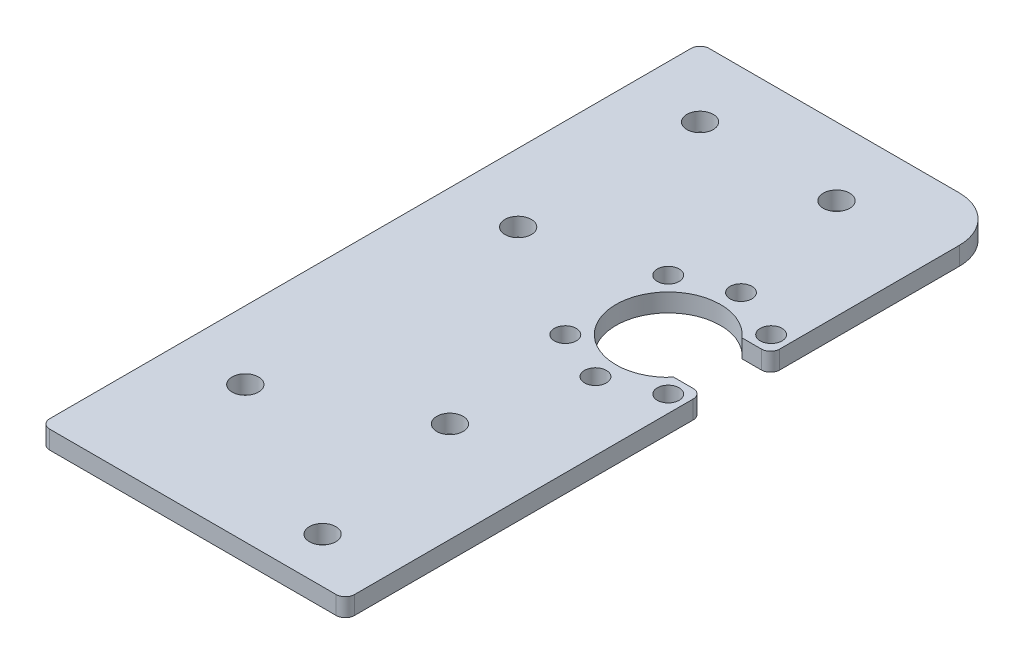
SolidWorks part; units mm, degrees
ref_plane "Front Plane" through (0, 0, 0) normal (0, 0, 1) x (1, 0, 0)
ref_plane "Top Plane" through (0, 0, 0) normal (0, 1, 0) x (1, 0, 0)
ref_plane "Right Plane" through (0, 0, 0) normal (1, 0, 0) x (0, 0, -1)
sketch "Sketch1" plane through (0, 0, 0) normal (0, 1, 0) x (1, 0, 0)
  line L1 (0, 0) -> (67, 0)
  line L2 (0, 0) -> (0, 145)
  line L3 (0, 145) -> (67, 145)
  line L4 (67, 0) -> (67, 145)
  dimension "D1" = 145
  dimension "D2" = 67
extrude "Boss-Extrude1" add sketch "Sketch1" along normal blind 4
sketch "Sketch2" plane through (0, 4, 0) normal (0, 1, 0) x (1, 0, 0)
  line L1 (0, 145) -> (0, 0) construction
  line L2 (60.7178, 78.5) -> (67, 78.5)
  line L3 (67, 0) -> (67, 145) construction
  line L4 (67, 78.5) -> (67, 93.5)
  line L5 (67, 93.5) -> (60.7178, 93.5)
  line L6 (52, 86) -> (67, 86) construction
  line L8 (67, 145) -> (0, 145) construction
  circle A0 centre (52, 86) radius 11.5
  dimension "D1" = 23
  dimension "D2" = 59
  dimension "D3" = 52
  dimension "D4" = 15
extrude "Cut-Extrude1" cut sketch "Sketch2" against normal through all
sketch "Sketch4" plane through (0, 4, 0) normal (0, 1, 0) x (1, 0, 0)
  line L0 (52, 86) -> (52, 70) construction
  line L1 (52, 86) -> (52, 102) construction
  line L2 (52, 86) -> (40.6863, 97.3137) construction
  line L3 (52, 86) -> (63.3137, 74.6863) construction
  line L4 (52, 86) -> (40.6863, 74.6863) construction
  line L5 (52, 86) -> (63.3137, 97.3137) construction
  line L7 (60.7178, 93.5) -> (67, 93.5)
  line L8 (67, 93.5) -> (67, 145)
  line L9 (67, 145) -> (0, 145)
  line L10 (0, 145) -> (0, 0)
  line L11 (0, 0) -> (67, 0)
  line L12 (67, 0) -> (67, 78.5)
  line L13 (67, 78.5) -> (60.7178, 78.5)
  line L14 (60.7178, 93.5) -> (67, 93.5)
  line L15 (67, 93.5) -> (67, 145)
  line L16 (67, 145) -> (0, 145)
  line L17 (0, 145) -> (0, 0)
  line L18 (0, 0) -> (67, 0)
  line L19 (67, 0) -> (67, 78.5)
  line L20 (67, 78.5) -> (60.7178, 78.5)
  circle A0 centre (63.3137, 97.3137) radius 2.4
  arc A1 (60.7178, 93.5) -> (60.7178, 78.5) centre (52, 86) ccw
  arc A2 (60.7178, 93.5) -> (60.7178, 78.5) centre (52, 86) ccw
  circle A3 centre (52, 102) radius 2.4
  circle A4 centre (40.6863, 97.3137) radius 2.4
  circle A5 centre (40.6863, 74.6863) radius 2.4
  circle A6 centre (52, 70) radius 2.4
  circle A7 centre (63.3137, 74.6863) radius 2.4
  circle A8 centre (52, 86) radius 16 construction
  dimension "D2" = 32
  dimension "D7" = 4.8
  dimension "D3" = 45
  dimension "D4" = 45
  dimension "D5" = 45
  dimension "D6" = 45
  dimension "D1" = 0
extrude "Cut-Extrude2" cut sketch "Sketch4" against normal through all contours A7 | A6 | A5 | A4 | A3 | A0
sketch "Sketch5" plane through (0, 4, 0) normal (0, 1, 0) x (1, 0, 0)
  line L0 (15, 130) -> (15, 145) construction
  line L1 (67, 145) -> (0, 145) construction
  line L2 (0, 145) -> (0, 0) construction
  line L3 (67, 0) -> (67, 78.5) construction
  line L4 (0, 0) -> (67, 0) construction
  line L5 (30, -10.3976) -> (30, 161.7631) construction
  line L6 (91.6272, -5) -> (-45.8391, -5) construction
  line L7 (52, 25) -> (52, 10) construction
  line L8 (67, -5) -> (37, -5) construction
  line L9 (67, -5) -> (67, 25) construction
  line L10 (67, 25) -> (37, 25) construction
  line L11 (37, -5) -> (37, 25) construction
  line L12 (60, 45) -> (45, 45) construction
  line L13 (30, 30) -> (60, 30) construction
  line L14 (30, 30) -> (30, 60) construction
  line L15 (30, 60) -> (60, 60) construction
  line L16 (60, 30) -> (60, 60) construction
  line L17 (60, 130) -> (45, 130) construction
  line L18 (30, 115) -> (60, 115) construction
  line L19 (30, 115) -> (30, 145) construction
  line L20 (30, 145) -> (60, 145) construction
  line L21 (60, 115) -> (60, 145) construction
  circle A0 centre (15, 130) radius 2.9
  circle A1 centre (15, 90) radius 2.9
  circle A3 centre (52, 10) radius 2.9
  circle A4 centre (15, 30) radius 2.9
  circle A5 centre (45, 130) radius 2.9
  circle A6 centre (45, 45) radius 2.9
  dimension "D2" = 5.8
  dimension "D1" = 15
  dimension "D3" = 15
  dimension "D4" = 45
  dimension "D5" = 100
  dimension "D6" = 40
  dimension "D7" = 60
  dimension "D8" = 30
  dimension "D9" = 15
  dimension "D10" = 10
  dimension "D11" = 5
  dimension "D12" = 30
  dimension "D13" = 30
  dimension "D14" = 30
  dimension "D15" = 30
  dimension "D16" = 30
  dimension "D17" = 30
extrude "Cut-Extrude3" cut sketch "Sketch5" against normal through all
fillet "Fillet1" radius 10 1 edges at (67, 2, -145)
fillet "Fillet2" radius 2 5 edges at (67, 2, -78.5) (67, 2, -93.5) (0, 2, -145) (0, 2, 0) (67, 2, 0)
